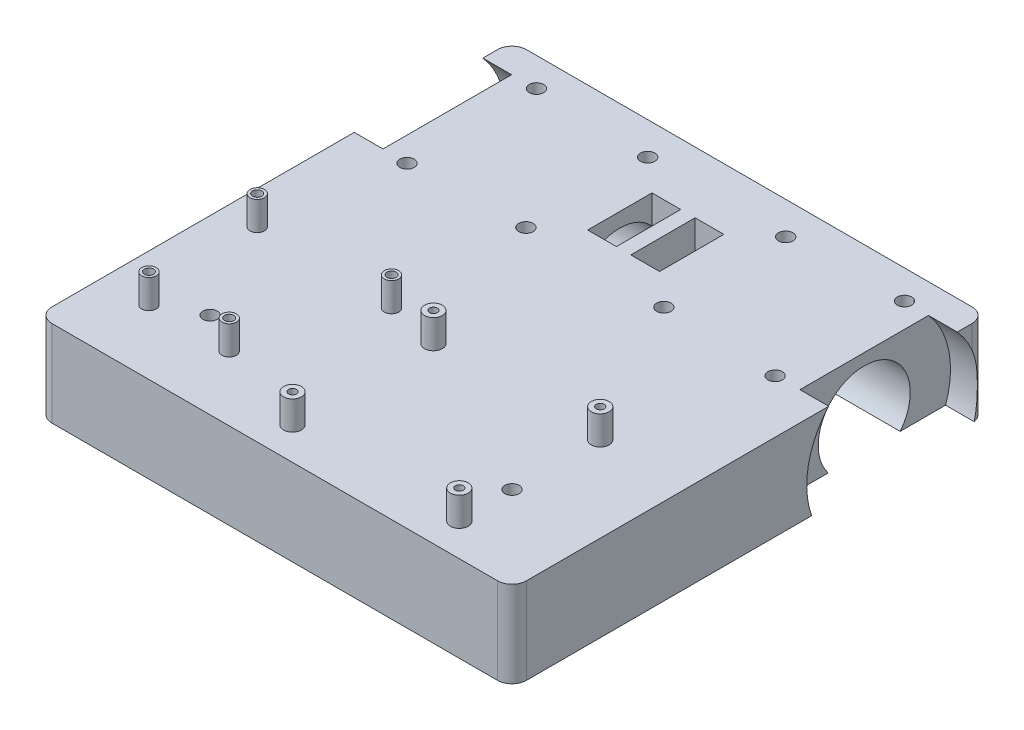
SolidWorks part; units mm, degrees
ref_plane "Plan de face" through (0, 0, 0) normal (0, 0, 1) x (1, 0, 0)
ref_plane "Plan de dessus" through (0, 0, 0) normal (0, 1, 0) x (1, 0, 0)
ref_plane "Plan de droite" through (0, 0, 0) normal (1, 0, 0) x (0, 0, -1)
sketch "Esquisse2" plane through (0, 0, 0) normal (0, 1, 0) x (1, 0, 0)
  line L1 (82.5, 82.5) -> (-82.5, 82.5)
  line L2 (82.5, 82.5) -> (82.5, -82.5)
  line L3 (82.5, -82.5) -> (-82.5, -82.5)
  line L4 (-82.5, 82.5) -> (-82.5, -82.5)
  line L5 (82.5, 82.5) -> (-82.5, -82.5) construction
  line L6 (82.5, -82.5) -> (-82.5, 82.5) construction
  point P0 (0, 0)
  dimension "D1" = 165
  dimension "D2" = 165
extrude "BASE" add sketch "Esquisse2" along normal blind 30
sketch "Esquisse3" plane through (82.5, 0, 0) normal (1, 0, 0) x (0, 0, -1)
  line L0 (82.5, 10) -> (31.0775, 10) construction
  line L1 (82.5, 30) -> (82.5, 0) construction
  line L2 (-82.5, 0) -> (82.5, 0) construction
  circle A0 centre (50, 10) radius 15
  point P4 (50, 10)
  dimension "D3" = 30
  dimension "D1" = 32.5
  dimension "D2" = 10
extrude "BLOC MOTEUR 1." cut sketch "Esquisse3" against normal blind 80
sketch "Esquisse4" plane through (0, 0, 0) normal (0, -1, 0) x (1, 0, 0)
  line L0 (2.5, -61.1803) -> (82.5, -61.1803) construction
  line L1 (2.5, -38.8197) -> (12.5, -38.8197)
  line L2 (2.5, -38.8197) -> (2.5, -61.1803)
  line L3 (2.5, -61.1803) -> (12.5, -61.1803)
  line L4 (12.5, -38.8197) -> (12.5, -61.1803)
  dimension "D1" = 10
extrude "ACCES MOTEUR" cut sketch "Esquisse4" against normal blind 37
ref_plane "PLAN SYM " through (0, 0, 0) normal (1, 0, 0) x (0, 0, -1)
sketch "Esquisse6" plane through (82.5, 0, 0) normal (1, 0, 0) x (0, 0, -1)
  line L0 (35, 10) -> (65, 10) construction
  arc A0 (38.8197, 20) -> (38.8197, 0) centre (50, 10) ccw construction
  arc A1 (61.1803, 0) -> (38.8197, 0) centre (50, 10) ccw construction
  circle A2 centre (50, 10) radius 16.01
  dimension "D1" = 32.02
extrude "BLOC MOTEUR 2" cut sketch "Esquisse6" against normal blind 37
mirror "SYM BLOC MOTEUR" about plane through (0, 0, 0) normal (1, 0, 0) of "ACCES MOTEUR", "BLOC MOTEUR 1.", "BLOC MOTEUR 2"
sketch "Esquisse7" plane through (0, 0, 0) normal (0, -1, 0) x (1, 0, 0)
  line L0 (-64, -37.4972) -> (-64, -72.5028) construction
  line L1 (-82.5, -37.4972) -> (-45.5, -37.4972) construction
  line L2 (-24, -38.8197) -> (-24, -67.469) construction
  line L3 (-45.5, -38.8197) -> (-2.5, -38.8197) construction
  line L4 (-45.5, -62.5028) -> (-82.5, -62.5028) construction
  line L5 (-2.5, -61.1803) -> (-45.5, -61.1803) construction
  line L6 (-64, -37.4972) -> (-64, -13.9891) construction
  line L7 (-24, -71.1803) -> (-24, -20.9291) construction
  circle A0 centre (-64, -27.4972) radius 2.5
  circle A1 centre (-24, -28.8197) radius 2.5
  circle A2 centre (-24, -71.1803) radius 2.5
  circle A3 centre (-64, -72.5028) radius 2.5
  point P8 (-64, -27.4972)
  point P9 (-64, -72.5028)
  point P10 (-24, -71.1803)
  point P11 (-24, -28.8197)
  dimension "D5" = 5
  dimension "D6" = 5
  dimension "D7" = 5
  dimension "D8" = 5
  dimension "D1" = 10
  dimension "D2" = 10
  dimension "D3" = 10
  dimension "D4" = 10
extrude "VIS MOTEUR" cut sketch "Esquisse7" against normal through all
mirror "SYM VIS" about plane through (0, 0, 0) normal (1, 0, 0) of "VIS MOTEUR"
sketch "Esquisse8" plane through (0, 0, 0) normal (0, -1, 0) x (1, 0, 0)
  line L0 (-82.5, 82.5) -> (82.5, 82.5) construction
  line L1 (-82.5, -37.4972) -> (-82.5, 82.5) construction
  line L2 (82.5, 82.5) -> (82.5, -37.4972) construction
  circle A0 centre (-52.5, 52.5) radius 2.5
  circle A1 centre (52.5, 52.5) radius 2.5
  point P0 (-52.5, 52.5)
  point P1 (52.5, 52.5)
  dimension "D5" = 5
  dimension "D6" = 5
  dimension "D1" = 30
  dimension "D2" = 30
  dimension "D3" = 30
  dimension "D4" = 30
extrude "VIS PATIN" cut sketch "Esquisse8" against normal through all
sketch "Esquisse9" plane through (0, 30, 0) normal (0, 1, 0) x (1, 0, 0)
  line L0 (-5.1247, -22.1943) -> (52.8753, -22.1943) construction
  line L1 (-5.1247, -71.1943) -> (52.8753, -71.1943) construction
  line L2 (52.8753, -22.1943) -> (52.8753, -70.2718) construction
  circle A0 centre (-5.1247, -22.1943) radius 1.375
  circle A1 centre (52.8753, -22.1943) radius 1.375
  circle A2 centre (52.8753, -71.1943) radius 1.375
  circle A3 centre (-5.1247, -71.1943) radius 1.375
  circle A4 centre (-5.1247, -22.1943) radius 3.1
  circle A5 centre (52.8753, -22.1943) radius 3.1
  circle A6 centre (-5.1247, -71.1943) radius 3.1
  circle A7 centre (52.8753, -71.1943) radius 3.1
  dimension "D1" = 2.75
  dimension "D2" = 2.75
  dimension "D3" = 2.75
  dimension "D4" = 2.75
  dimension "D9" = 6.2
  dimension "D10" = 6.2
  dimension "D11" = 6.2
  dimension "D12" = 6.2
  dimension "D5" = 58
  dimension "D6" = 58
  dimension "D7" = 49
extrude "SUPPORT RASP" add sketch "Esquisse9" along normal blind 10
sketch "Esquisse11" plane through (0, 30, 0) normal (0, 1, 0) x (1, 0, 0)
  circle A0 centre (-70.9338, -17.6706) radius 1.6
  circle A1 centre (-70.9338, -17.6706) radius 2.5
  circle A2 centre (-23.1238, -18.7706) radius 1.6
  circle A3 centre (-23.1238, -18.7706) radius 2.5
  circle A4 centre (-66.2338, -60.0106) radius 1.6
  circle A5 centre (-66.2338, -60.0106) radius 2.5
  circle A6 centre (-38.3338, -60.0106) radius 1.6
  circle A7 centre (-38.3338, -60.0106) radius 2.5
  point P0 (-66.2338, -60.0106)
  point P1 (-38.3338, -60.0106)
  point P2 (-23.1238, -18.7706)
  point P3 (-70.9338, -17.6706)
  dimension "D8" = 3.2
  dimension "D9" = 5
  dimension "D10" = 3.2
  dimension "D11" = 5
  dimension "D12" = 3.2
  dimension "D13" = 3.2
  dimension "D14" = 5
  dimension "D15" = 5
  dimension "D1" = 4.7
  dimension "D2" = 47.81
  dimension "D3" = 15.21
  dimension "D4" = 27.9
  dimension "D5" = 41.24
  dimension "D6" = 42.34
  dimension "D7" = 0
extrude "SUPPORT ARDUINO" add sketch "Esquisse11" along normal blind 10
fillet "CONGE EXT" radius 5 4 edges at (82.5, 15, 82.5) (82.5, 15, -82.5) (-82.5, 15, -82.5) (-82.5, 15, 82.5)
sketch "Esquisse12" plane through (-82.5, 0, 0) normal (-1, 0, 0) x (0, 0, 1)
  circle A0 centre (-50, 10) radius 30
  dimension "D1" = 60
extrude "ESPACE ROUE " cut sketch "Esquisse12" against normal blind 10
mirror "SYM ESPACE ROUE" about plane through (0, 0, 0) normal (1, 0, 0) of "ESPACE ROUE "
